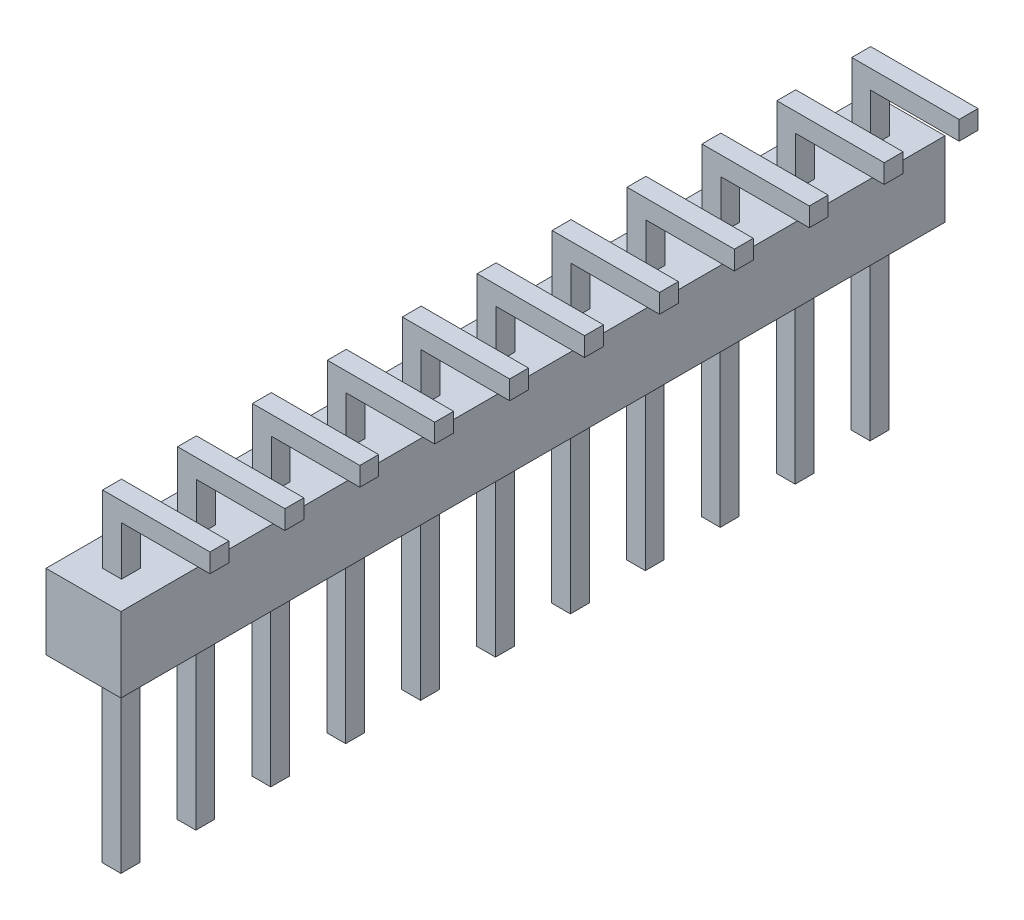
SolidWorks part; units mm, degrees
ref_plane "Front Plane" through (0, 0, 0) normal (0, 0, 1) x (1, 0, 0)
ref_plane "Top Plane" through (0, 0, 0) normal (0, 1, 0) x (1, 0, 0)
ref_plane "Right Plane" through (0, 0, 0) normal (1, 0, 0) x (0, 0, -1)
sketch "Sketch1" plane through (0, 0, 0) normal (0, 0, 1) x (1, 0, 0)
  line L1 (0, 0) -> (2.54, 0)
  line L2 (0, 0) -> (0, 2.54)
  line L3 (0, 2.54) -> (2.54, 2.54)
  line L4 (2.54, 0) -> (2.54, 2.54)
  dimension "D1" = 2.54
  dimension "D2" = 2.54
extrude "Boss-Extrude1" add sketch "Sketch1" along normal blind 27.94
sketch "Sketch2" plane through (0, 0, 0) normal (0, -1, 0) x (1, 0, 0)
  line L0 (0, 27.94) -> (2.54, 27.94) construction
  line L1 (0.95, 26.99) -> (1.59, 26.99)
  line L2 (0.95, 26.99) -> (0.95, 26.35)
  line L3 (0.95, 26.35) -> (1.59, 26.35)
  line L4 (1.59, 26.99) -> (1.59, 26.35)
  line L5 (0, 27.94) -> (0, 0) construction
  dimension "D1" = 0.64
  dimension "D2" = 0.64
  dimension "D3" = 0.95
  dimension "D4" = 0.95
extrude "Boss-Extrude2" add sketch "Sketch2" along normal blind 6.1
pattern_linear "LPattern1" count 11 spacing 2.54 along (0, 0, -1) of "Boss-Extrude2"
sketch "Sketch3" plane through (0, 2.54, 0) normal (0, 1, 0) x (1, 0, 0)
  line L0 (2.54, 0) -> (0, 0) construction
  line L1 (0.96, -1.58) -> (1.6, -1.58)
  line L2 (0.96, -1.58) -> (0.96, -0.94)
  line L3 (0.96, -0.94) -> (1.6, -0.94)
  line L4 (1.6, -1.58) -> (1.6, -0.94)
  line L5 (2.54, -27.94) -> (2.54, 0) construction
  dimension "D1" = 0.64
  dimension "D2" = 0.64
  dimension "D3" = 0.94
  dimension "D4" = 0.94
extrude "Boss-Extrude3" add sketch "Sketch3" along normal blind 2.3
pattern_linear "LPattern2" count 11 spacing 2.54 along (0, 0, 1) of "Boss-Extrude3"
sketch "Sketch4" plane through (1.6, 0, 0) normal (1, 0, 0) x (0, 0, -1)
  line L0 (-1.58, 4.84) -> (-1.58, 2.54) construction
  line L1 (-0.94, 4.84) -> (-1.58, 4.84)
  line L2 (-0.94, 4.84) -> (-0.94, 4.2)
  line L3 (-0.94, 4.2) -> (-1.58, 4.2)
  line L4 (-1.58, 4.84) -> (-1.58, 4.2)
  dimension "D1" = 0.64
extrude "Boss-Extrude4" add sketch "Sketch4" along normal blind 3
pattern_linear "LPattern3" count 11 spacing 2.54 along (0, 0, 1) of "Boss-Extrude4"
